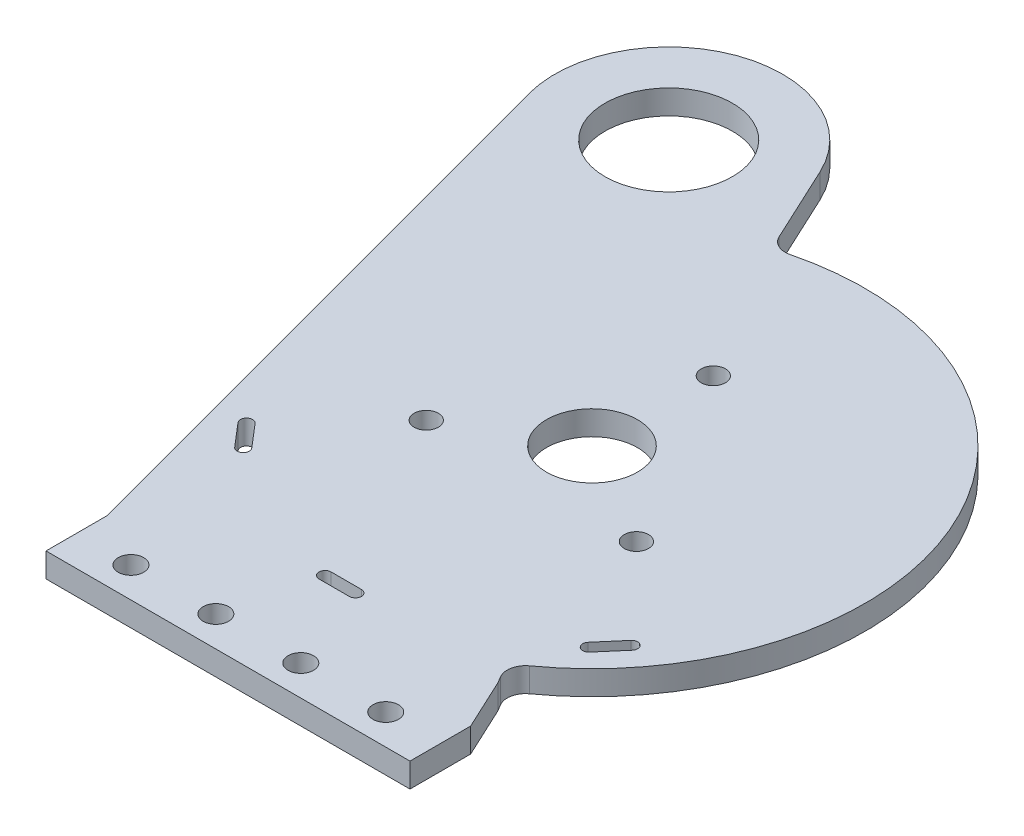
SolidWorks part; units mm, degrees
ref_plane "前视基准面" through (0, 0, 0) normal (0, 0, 1) x (1, 0, 0)
ref_plane "上视基准面" through (0, 0, 0) normal (0, 1, 0) x (1, 0, 0)
ref_plane "右视基准面" through (0, 0, 0) normal (1, 0, 0) x (0, 0, -1)
sketch "草图1" plane through (0, 0, 0) normal (0, 1, 0) x (1, 0, 0)
  line L0 (-106.0169, 0) -> (157.3729, 0) construction
  line L1 (0, 80.0847) -> (0, -75) construction
  line L2 (0, 10) -> (0, 0)
  line L3 (0, 0) -> (60, 0)
  line L4 (60, 0) -> (60, 10)
  line L5 (0, 10) -> (-81.05, 312.4827) construction
  line L6 (-81.05, 312.4827) -> (60, 10) construction
  line L7 (0, 10) -> (-25.4925, 105.1394)
  line L8 (9.6682, 117.9368) -> (15.5695, 105.2815)
  line L9 (30, -37.7788) -> (30, 40.3005) construction
  line L10 (30, 60) -> (120.612, 7.6851) construction
  line L11 (30, 60) -> (-80.725, -3.9271) construction
  line L12 (56.0952, 18.3739) -> (60, 10)
  line L13 (-20.8285, 5) -> (77.5861, 5) construction
  line L14 (55.4312, 19.5) -> (56.0952, 18.3739)
  line L15 (26.5, 19.5) -> (31.5, 19.5) construction
  line L16 (26.5, 20.5) -> (31.5, 20.5)
  line L17 (26.5, 18.5) -> (31.5, 18.5)
  line L18 (30, 60) -> (0, 34.3047) construction
  line L19 (-1.7353, 34.7934) -> (1.5173, 30.9959) construction
  line L20 (-0.9758, 35.4439) -> (2.2768, 31.6464)
  line L21 (-2.4948, 34.1429) -> (0.7578, 30.3454)
  line L22 (61.7353, 34.7934) -> (58.4827, 30.9959) construction
  line L23 (60.9758, 35.4439) -> (57.7232, 31.6464)
  line L24 (62.4948, 34.1429) -> (59.2422, 30.3454)
  arc A0 (-25.4925, 105.1394) -> (9.6682, 117.9368) centre (-7.3523, 110) cw
  circle A1 centre (-7.3523, 110) radius 10.5
  circle A2 centre (30, 60) radius 39.5 construction
  circle A3 centre (30, 60) radius 41.5 construction
  circle A4 centre (30, 60) radius 7.5
  circle A5 centre (30, 60) radius 20 construction
  circle A6 centre (30, 80) radius 2
  circle A7 centre (47.3205, 50) radius 2
  circle A8 centre (12.6795, 50) radius 2
  arc A9 (19.0204, 103.64) -> (56.2644, 23.4598) centre (30, 60) cw
  circle A10 centre (23, 5) radius 2.1
  circle A11 centre (9, 5) radius 2.1
  circle A12 centre (37, 5) radius 2.1
  circle A13 centre (51, 5) radius 2.1
  arc A14 (55.4312, 19.5) -> (56.2644, 23.4598) centre (58.0153, 21.0238) cw
  arc A15 (15.5695, 105.2815) -> (19.0204, 103.64) centre (18.2884, 106.5493) ccw
  arc A16 (26.5, 20.5) -> (26.5, 18.5) centre (26.5, 19.5) ccw
  arc A17 (31.5, 18.5) -> (31.5, 20.5) centre (31.5, 19.5) ccw
  arc A18 (-0.9758, 35.4439) -> (-2.4948, 34.1429) centre (-1.7353, 34.7934) ccw
  arc A19 (0.7578, 30.3454) -> (2.2768, 31.6464) centre (1.5173, 30.9959) ccw
  arc A20 (60.9758, 35.4439) -> (62.4948, 34.1429) centre (61.7353, 34.7934) cw
  arc A21 (59.2422, 30.3454) -> (57.7232, 31.6464) centre (58.4827, 30.9959) cw
  point P15 (30, 0)
  point P36 (0, 5)
  point P50 (29, 19.5)
  point P58 (-0.109, 32.8947)
  point P63 (0, 0)
  point P64 (-0.3505, 32.7696)
  point P65 (-3.2779, 33.5111)
  point P66 (0.3565, 32.2553)
  point P67 (0, 0)
  point P68 (0.3565, 32.2553)
  point P69 (0.3565, 32.2553)
  point P70 (0.3565, 32.2553)
  point P71 (0.3565, 32.2553)
  point P74 (60.109, 32.8947)
  dimension "D7" = 21
  dimension "D8" = 60
  dimension "D11" = 40
  dimension "D12" = 15
  dimension "D13" = 4
  dimension "D14" = 45
  dimension "D15" = 4.2
  dimension "D18" = 3
  dimension "D9" = 120
  dimension "D19" = 3
  dimension "D20" = 79
  dimension "D21" = 83
  dimension "D22" = 2
  dimension "D23" = 5
  dimension "D24" = 1
  dimension "D25" = 5
  dimension "D26" = 1
  dimension "D1" = 60
  dimension "D2" = 10
  dimension "D3" = 10
  dimension "D4" = 15
  dimension "D5" = 25
  dimension "D6" = 110
  dimension "D10" = 120
  dimension "D16" = 7
  dimension "D17" = 14
  dimension "D27" = 1
extrude "凸台-拉伸1" add sketch "草图1" along normal blind 4
